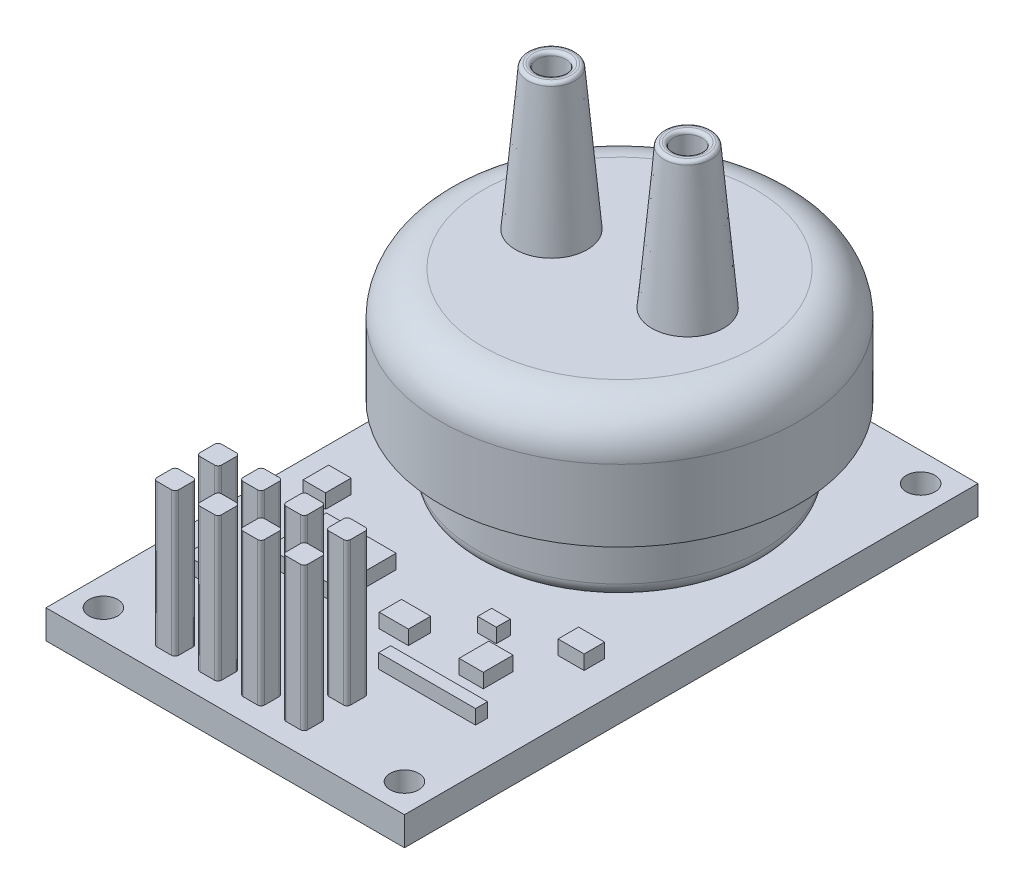
SolidWorks part; units mm, degrees
ref_plane "Front Plane" through (0, 0, 0) normal (0, 0, 1) x (1, 0, 0)
ref_plane "Top Plane" through (0, 0, 0) normal (0, 1, 0) x (1, 0, 0)
ref_plane "Right Plane" through (0, 0, 0) normal (1, 0, 0) x (0, 0, -1)
sketch "Sketch1" plane through (0, 0, 0) normal (0, 1, 0) x (1, 0, 0)
  line L0 (0, 0) -> (0, -40) construction
  line L1 (-12.5, 0) -> (12.5, 0)
  line L2 (-12.5, 0) -> (-12.5, -40)
  line L3 (-12.5, -40) -> (12.5, -40)
  line L4 (12.5, 0) -> (12.5, -40)
  line L5 (12.5, -20) -> (-12.5, -20) construction
  circle A0 centre (-10.5, -2) radius 1
  circle A1 centre (10.5, -2) radius 1
  circle A2 centre (10.5, -38) radius 1
  circle A3 centre (-10.5, -38) radius 1
  point P4 (0, 0)
  point P17 (0, 0)
  point P18 (0, 0)
  dimension "D5" = 2
  dimension "D1" = 25
  dimension "D2" = 40
  dimension "D3" = 2
  dimension "D4" = 2
extrude "Boss-Extrude1" add sketch "Sketch1" along normal blind 2
sketch "Sketch3" plane through (0, 0, 0) normal (1, 0, 0) x (0, 0, -1)
  line L5 (-12.5, -8.5674) -> (-12.5, 24.8999) construction
  line L6 (0, 2) -> (0, 0) construction
  line L7 (-12.5, 2) -> (-3.5, 2)
  line L8 (-40, 2) -> (0, 2) construction
  line L9 (-2.5, 3) -> (-2.5, 6)
  line L10 (-1.5, 7) -> (0, 7)
  line L11 (0, 7) -> (0, 12)
  line L12 (-3, 15) -> (-12.5, 15)
  line L13 (-12.5, 2) -> (-12.5, 15)
  arc A0 (-2.5, 6) -> (-1.5, 7) centre (-1.5, 6) cw
  arc A1 (-3.5, 2) -> (-2.5, 3) centre (-3.5, 3) ccw
  arc A2 (0, 12) -> (-3, 15) centre (-3, 12) ccw
  point P17 (-2.5, 2)
  dimension "D2" = 1
  dimension "D3" = 1
  dimension "D4" = 3
  dimension "D1" = 12.5
  dimension "D5" = 8
  dimension "D6" = 5
  dimension "D7" = 10
revolve "Revolve1" add sketch "Sketch3" angle 360 about L5
sketch "Sketch4" plane through (0, 15, 0) normal (0, 1, 0) x (1, 0, 0)
  line L0 (-9.5, -12.5) -> (9.5, -12.5) construction
  line L1 (0, -3) -> (0, -22) construction
  line L2 (-9.5, -12.5) -> (0, -12.5) construction
  line L3 (0, -12.5) -> (9.5, -12.5) construction
  circle A0 centre (0, -12.5) radius 9.5 construction
  circle A1 centre (4.75, -12.5) radius 2.5
  circle A2 centre (-4.75, -12.5) radius 2.5
  dimension "D1" = 5
extrude "Boss-Extrude2" add sketch "Sketch4" along normal blind 10 draft 5
sketch "Sketch5" plane through (0, 25, 0) normal (0, 1, 0) x (1, 0, 0)
  circle A0 centre (-4.75, -12.5) radius 1
  circle A1 centre (4.75, -12.5) radius 1
  dimension "D1" = 2
  dimension "D2" = 2
extrude "Cut-Extrude1" cut sketch "Sketch5" against normal blind 10
fillet "Fillet1" radius 0.25 4 edges at (-4.75, 25, 10.8749) (-4.75, 25, 13.5) (4.75, 25, 14.1251) (4.75, 25, 13.5)
sketch "Sketch6" plane through (0, 2, 0) normal (0, 1, 0) x (1, 0, 0)
  line L1 (-7.4566, -25.4943) -> (-2.584, -25.4943)
  line L2 (-7.4566, -25.4943) -> (-7.4566, -29.6502)
  line L3 (-7.4566, -29.6502) -> (-2.584, -29.6502)
  line L4 (-2.584, -25.4943) -> (-2.584, -29.6502)
  line L5 (5.9579, -27.5722) -> (7.6492, -27.5722)
  line L6 (5.9579, -27.5722) -> (5.9579, -29.6502)
  line L7 (5.9579, -29.6502) -> (7.6492, -29.6502)
  line L8 (7.6492, -27.5722) -> (7.6492, -29.6502)
  line L9 (0.3893, -28.0966) -> (2.4252, -28.0966)
  line L10 (0.3893, -28.0966) -> (0.3893, -29.6502)
  line L11 (0.3893, -29.6502) -> (2.4252, -29.6502)
  line L12 (2.4252, -28.0966) -> (2.4252, -29.6502)
  line L13 (4.0716, -25.4943) -> (5.3751, -25.4943)
  line L14 (4.0716, -25.4943) -> (4.0716, -26.4719)
  line L15 (4.0716, -26.4719) -> (5.3751, -26.4719)
  line L16 (5.3751, -25.4943) -> (5.3751, -26.4719)
  line L17 (8.2377, -23.5951) -> (10.0564, -23.5951)
  line L18 (8.2377, -23.5951) -> (8.2377, -25.0276)
  line L19 (8.2377, -25.0276) -> (10.0564, -25.0276)
  line L20 (10.0564, -23.5951) -> (10.0564, -25.0276)
  line L21 (-10.2618, -22.5261) -> (-8.6948, -22.5261)
  line L22 (-10.2618, -22.5261) -> (-10.2618, -24.3113)
  line L23 (-10.2618, -24.3113) -> (-8.6948, -24.3113)
  line L24 (-8.6948, -22.5261) -> (-8.6948, -24.3113)
  line L25 (-9.8742, -31.2751) -> (-8.6948, -31.2751)
  line L26 (-9.8742, -31.2751) -> (-9.8742, -32.9475)
  line L27 (-9.8742, -32.9475) -> (-8.6948, -32.9475)
  line L28 (-8.6948, -31.2751) -> (-8.6948, -32.9475)
  line L29 (2.812, -31.2751) -> (9.5693, -31.2751)
  line L30 (2.812, -31.2751) -> (2.812, -32.1113)
  line L31 (2.812, -32.1113) -> (9.5693, -32.1113)
  line L32 (9.5693, -31.2751) -> (9.5693, -32.1113)
extrude "Boss-Extrude3" add sketch "Sketch6" along normal blind 1
sketch "Sketch7" plane through (0, 2, 0) normal (0, 1, 0) x (1, 0, 0)
  line L0 (-12.5, -40) -> (12.5, -40) construction
  line L1 (-6.5, -34) -> (8.5, -34) construction
  line L2 (-6.5, -34) -> (-6.5, -38) construction
  line L3 (-6.5, -38) -> (8.5, -38) construction
  line L4 (8.5, -34) -> (8.5, -38) construction
  line L5 (12.5, -40) -> (12.5, 0) construction
  line L6 (-12.5, 0) -> (-12.5, -40) construction
  line L8 (-6.25, -34) -> (-5.25, -34)
  line L9 (-6.5, -34.25) -> (-6.5, -35.25)
  line L10 (-6.25, -35.5) -> (-5.25, -35.5)
  line L11 (-5, -34.25) -> (-5, -35.25)
  line L16 (-3.5, -34.25) -> (-3.5, -35.25)
  line L17 (-3.25, -34) -> (-2.25, -34)
  line L18 (-2, -34.25) -> (-2, -35.25)
  line L19 (-3.25, -35.5) -> (-2.25, -35.5)
  line L20 (-0.5, -34.25) -> (-0.5, -35.25)
  line L21 (-0.25, -34) -> (0.75, -34)
  line L22 (1, -34.25) -> (1, -35.25)
  line L23 (-0.25, -35.5) -> (0.75, -35.5)
  line L24 (2.5, -34.25) -> (2.5, -35.25)
  line L25 (2.75, -34) -> (3.75, -34)
  line L26 (4, -34.25) -> (4, -35.25)
  line L27 (2.75, -35.5) -> (3.75, -35.5)
  line L28 (-3.5, -37.25) -> (-3.5, -38.25)
  line L29 (-3.25, -37) -> (-2.25, -37)
  line L30 (-2, -37.25) -> (-2, -38.25)
  line L31 (-3.25, -38.5) -> (-2.25, -38.5)
  line L32 (-0.5, -37.25) -> (-0.5, -38.25)
  line L33 (-0.25, -37) -> (0.75, -37)
  line L34 (1, -37.25) -> (1, -38.25)
  line L35 (-0.25, -38.5) -> (0.75, -38.5)
  line L36 (2.5, -37.25) -> (2.5, -38.25)
  line L37 (2.75, -37) -> (3.75, -37)
  line L38 (4, -37.25) -> (4, -38.25)
  line L39 (2.75, -38.5) -> (3.75, -38.5)
  line L40 (-6.5, -37.25) -> (-6.5, -38.25)
  line L41 (-6.25, -37) -> (-5.25, -37)
  line L42 (-5, -37.25) -> (-5, -38.25)
  line L43 (-6.25, -38.5) -> (-5.25, -38.5)
  arc A4 (-6.5, -35.25) -> (-6.25, -35.5) centre (-6.25, -35.25) ccw
  arc A5 (-6.25, -34) -> (-6.5, -34.25) centre (-6.25, -34.25) ccw
  arc A6 (-5.25, -34) -> (-5, -34.25) centre (-5.25, -34.25) cw
  arc A7 (-5.25, -35.5) -> (-5, -35.25) centre (-5.25, -35.25) ccw
  arc A8 (-3.25, -34) -> (-3.5, -34.25) centre (-3.25, -34.25) ccw
  arc A9 (-3.5, -35.25) -> (-3.25, -35.5) centre (-3.25, -35.25) ccw
  arc A10 (-2.25, -34) -> (-2, -34.25) centre (-2.25, -34.25) cw
  arc A11 (-2.25, -35.5) -> (-2, -35.25) centre (-2.25, -35.25) ccw
  arc A12 (-0.25, -34) -> (-0.5, -34.25) centre (-0.25, -34.25) ccw
  arc A13 (-0.5, -35.25) -> (-0.25, -35.5) centre (-0.25, -35.25) ccw
  arc A14 (0.75, -34) -> (1, -34.25) centre (0.75, -34.25) cw
  arc A15 (0.75, -35.5) -> (1, -35.25) centre (0.75, -35.25) ccw
  arc A16 (2.75, -34) -> (2.5, -34.25) centre (2.75, -34.25) ccw
  arc A17 (2.5, -35.25) -> (2.75, -35.5) centre (2.75, -35.25) ccw
  arc A18 (3.75, -34) -> (4, -34.25) centre (3.75, -34.25) cw
  arc A19 (3.75, -35.5) -> (4, -35.25) centre (3.75, -35.25) ccw
  arc A20 (-3.25, -37) -> (-3.5, -37.25) centre (-3.25, -37.25) ccw
  arc A21 (-3.5, -38.25) -> (-3.25, -38.5) centre (-3.25, -38.25) ccw
  arc A22 (-2.25, -37) -> (-2, -37.25) centre (-2.25, -37.25) cw
  arc A23 (-2.25, -38.5) -> (-2, -38.25) centre (-2.25, -38.25) ccw
  arc A24 (-0.25, -37) -> (-0.5, -37.25) centre (-0.25, -37.25) ccw
  arc A25 (-0.5, -38.25) -> (-0.25, -38.5) centre (-0.25, -38.25) ccw
  arc A26 (0.75, -37) -> (1, -37.25) centre (0.75, -37.25) cw
  arc A27 (0.75, -38.5) -> (1, -38.25) centre (0.75, -38.25) ccw
  arc A28 (2.75, -37) -> (2.5, -37.25) centre (2.75, -37.25) ccw
  arc A29 (2.5, -38.25) -> (2.75, -38.5) centre (2.75, -38.25) ccw
  arc A30 (3.75, -37) -> (4, -37.25) centre (3.75, -37.25) cw
  arc A31 (3.75, -38.5) -> (4, -38.25) centre (3.75, -38.25) ccw
  arc A32 (-6.25, -37) -> (-6.5, -37.25) centre (-6.25, -37.25) ccw
  arc A33 (-6.5, -38.25) -> (-6.25, -38.5) centre (-6.25, -38.25) ccw
  arc A34 (-5.25, -37) -> (-5, -37.25) centre (-5.25, -37.25) cw
  arc A35 (-5.25, -38.5) -> (-5, -38.25) centre (-5.25, -38.25) ccw
  point P45 (-5, -38)
  point P50 (-6.5, -36.5)
  point P53 (-6.5, -35.5)
  point P59 (-5, -34)
  dimension "D10" = 2
  dimension "D14" = 0.25
  dimension "D15" = 0.25
  dimension "D16" = 0.25
  dimension "D17" = 0.25
  dimension "D1" = 2
  dimension "D2" = 4
  dimension "D3" = 6
  dimension "D4" = 4
  dimension "D5" = 1.5
  dimension "D6" = 1.5
  dimension "D7" = 1.5
  dimension "D8" = 1.5
  dimension "D9" = 4
extrude "Boss-Extrude4" add sketch "Sketch7" along normal blind 10
